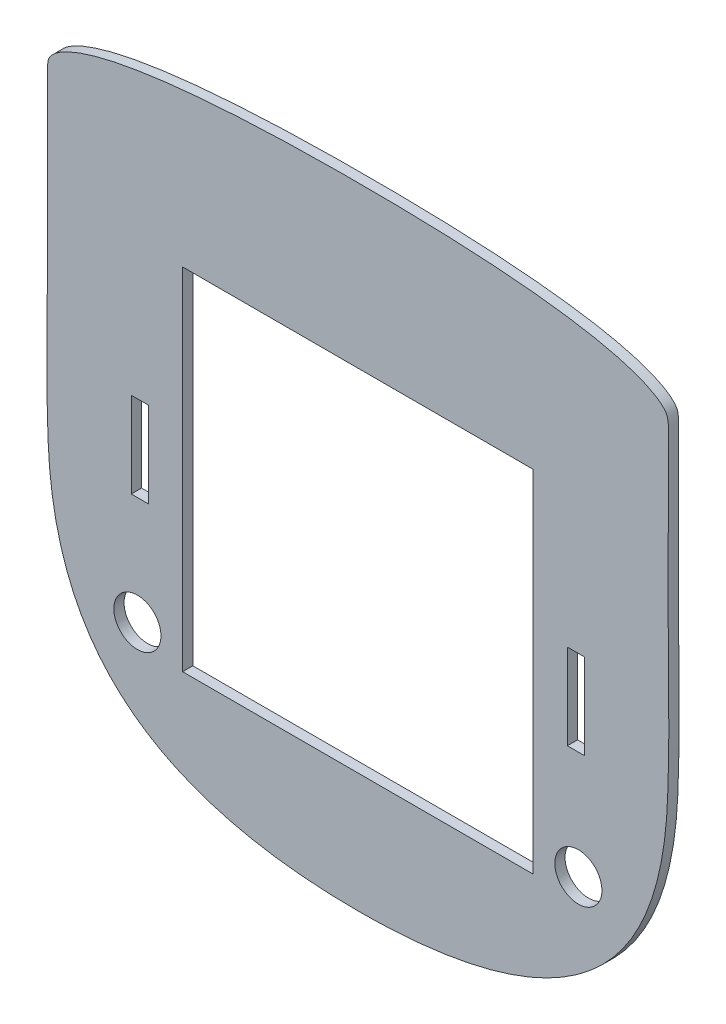
SolidWorks part; units mm, degrees
ref_plane "Front Plane" through (0, 0, 0) normal (0, 0, 1) x (1, 0, 0)
ref_plane "Top Plane" through (0, 0, 0) normal (0, 1, 0) x (1, 0, 0)
ref_plane "Right Plane" through (0, 0, 0) normal (1, 0, 0) x (0, 0, -1)
sketch "Sketch2" plane through (-0.2017, -72.2355, -2871.2971) normal (0, 0, 1) x (1, 0, 0)
  line L4 (52.07, 67.2522) -> (-52.07, 67.2522)
  line L5 (-52.07, 67.2522) -> (-52.07, -36.8878)
  line L6 (52.07, -36.8878) -> (52.07, 67.2522)
  line L7 (-52.07, -36.8878) -> (52.07, -36.8878)
  line L8 (0, 67.2522) -> (0, 47.5498)
  line L9 (-67.31, 26.6122) -> (-62.23, 26.6122)
  line L10 (-67.31, 26.6122) -> (-67.31, 1.2122)
  line L11 (-67.31, 1.2122) -> (-62.23, 1.2122)
  line L12 (-62.23, 26.6122) -> (-62.23, 1.2122)
  line L13 (67.31, 1.2122) -> (62.23, 1.2122)
  line L14 (67.31, 26.6122) -> (62.23, 26.6122)
  line L15 (62.23, 26.6122) -> (62.23, 1.2122)
  line L16 (67.31, 26.6122) -> (67.31, 1.2122)
  circle A3 centre (65.5, -30.8878) radius 7
  circle A4 centre (-65.5, -30.8878) radius 7
  spline S0 degree 3 poles (97.9117, 101.757) (98.0926, 100.5826) (98.1683, 99.8507) (98.201, 98.9643) (98.2056, 98.5204) (98.2033, 98.0762) (98.2036, 97.6318) (98.2026, 97.1872) (98.2018, 96.5942) (98.1997, 95.5557) (98.1964, 94.0701) (98.1912, 92.2844) (98.1853, 90.4955) (98.1786, 88.7035) (98.1713, 86.9085) (98.1636, 85.1105) (98.1554, 83.3094) (98.147, 81.5054) (98.1356, 79.096) (98.1213, 76.0769) (98.1051, 72.4424) (98.0908, 68.7965) (98.0796, 65.1394) (98.0728, 61.4713) (98.0711, 57.7925) (98.0753, 54.103) (98.0874, 50.4033) (98.1094, 46.6935) (98.1491, 41.7343) (98.2125, 35.5119) (98.2598, 28.01) (98.2502, 21.7312) (98.1939, 16.6943) (98.1345, 13.5409) (98.0699, 11.0154) (98.0125, 9.1199) (97.945, 7.2235) (97.8675, 5.3262) (97.778, 3.4282) (97.6786, 1.5298) (97.5624, -0.3688) (97.2739, -4.1659) (96.6367, -9.8576) (95.2643, -17.3922) (93.2832, -24.8169) (90.6142, -32.0401) (87.1877, -38.9585) (83.6766, -44.3599) (80.4862, -48.4025) (77.0545, -52.2409) (72.332, -56.6273) (66.103, -61.1882) (59.4287, -65.0467) (52.4324, -68.2445) (45.1957, -70.832) (37.7973, -72.8633) (30.2897, -74.3932) (22.7275, -75.4943) (12.6127, -76.4627) (5.0324, -76.7148) (-5.0355, -76.7148) (-12.6198, -76.4624) (-22.7388, -75.4931) (-30.3035, -74.391) (-37.8129, -72.8599) (-45.2125, -70.8272) (-52.4499, -68.238) (-59.4461, -65.0384) (-66.1196, -61.178) (-72.3471, -56.6154) (-77.0679, -52.2278) (-80.4981, -48.3887) (-83.6868, -44.3454) (-87.1957, -38.9438) (-90.6199, -32.0257) (-93.2868, -24.8034) (-95.2663, -17.38) (-96.6374, -9.847) (-97.2741, -4.1565) (-97.5622, -0.3603) (-97.6784, 1.5379) (-97.7779, 3.4359) (-97.8674, 5.3334) (-97.9449, 7.2303) (-98.0124, 9.1263) (-98.0698, 11.0213) (-98.1344, 13.5463) (-98.1939, 16.699) (-98.2502, 21.7349) (-98.2598, 28.0124) (-98.2124, 35.5129) (-98.1491, 41.7344) (-98.1094, 46.6929) (-98.0874, 50.4022) (-98.0753, 54.1015) (-98.0711, 57.7907) (-98.0728, 61.4693) (-98.0796, 65.1372) (-98.0908, 68.7942) (-98.1051, 72.44) (-98.1213, 76.0745) (-98.1356, 79.0937) (-98.147, 81.5032) (-98.1554, 83.3073) (-98.1636, 85.1085) (-98.1713, 86.9067) (-98.1786, 88.7018) (-98.1853, 90.494) (-98.1912, 92.283) (-98.1963, 94.069) (-98.1997, 95.5548) (-98.2018, 96.5934) (-98.2026, 97.1865) (-98.2036, 97.6312) (-98.2034, 98.0756) (-98.2056, 98.5199) (-98.201, 98.9639) (-98.1685, 99.8505) (-98.0927, 100.5825) (-97.9118, 101.7567) (-97.5911, 102.9272) (-96.7445, 104.5237) (-95.6284, 105.9307) (-94.3242, 107.1498) (-92.9089, 108.2104) (-90.9195, 109.4482) (-88.322, 110.7311) (-85.1289, 111.981) (-81.907, 113.0191) (-78.6797, 113.8993) (-75.4586, 114.6561) (-72.2483, 115.315) (-69.0513, 115.893) (-65.8677, 116.4036) (-62.6974, 116.856) (-59.5401, 117.2586) (-55.346, 117.7364) (-50.1305, 118.2378) (-43.9049, 118.7183) (-37.6983, 119.1001) (-31.4972, 119.4014) (-25.2861, 119.6319) (-19.0497, 119.8026) (-10.6783, 119.9573) (-4.3114, 120) (4.3116, 120) (10.6784, 119.9573) (19.0492, 119.8026) (25.285, 119.6319) (31.4954, 119.4014) (37.6957, 119.1003) (43.9016, 118.7185) (50.1264, 118.2381) (55.3414, 117.7368) (59.535, 117.2592) (62.6921, 116.8566) (65.8622, 116.4044) (69.0457, 115.8939) (72.2427, 115.316) (75.4529, 114.6572) (78.6742, 113.9005) (81.9018, 113.0204) (85.1241, 111.9825) (88.3177, 110.7327) (90.916, 109.4498) (92.906, 108.212) (94.3218, 107.1513) (95.6266, 105.9321) (96.7434, 104.5248) (97.5906, 102.9279) (97.9117, 101.757) (98.0926, 100.5826) (98.1683, 99.8507) knots -0.005356 -0.002678 0 0 0.002568 0.00321 0.003852 0.004494 0.005135 0.005777 0.006419 0.007703 0.010271 0.012839 0.015406 0.017974 0.020542 0.02311 0.025677 0.028245 0.030813 0.035948 0.041084 0.046219 0.051355 0.05649 0.061626 0.066761 0.071897 0.077032 0.082168 0.092439 0.10271 0.112981 0.118116 0.123252 0.125819 0.128387 0.130955 0.133522 0.13609 0.138658 0.141226 0.143793 0.154064 0.164335 0.174606 0.184877 0.195148 0.205419 0.210555 0.21569 0.225961 0.236232 0.246503 0.256774 0.267045 0.277316 0.287587 0.297858 0.308129 0.328671 0.328671 0.349207 0.359475 0.369743 0.380011 0.390279 0.400547 0.410816 0.421084 0.431352 0.44162 0.446754 0.451888 0.462156 0.472424 0.482692 0.492961 0.503229 0.513497 0.516064 0.518631 0.521198 0.523765 0.526332 0.528899 0.531466 0.534033 0.539167 0.544301 0.554569 0.564837 0.575105 0.580239 0.585374 0.590508 0.595642 0.600776 0.60591 0.611044 0.616178 0.621312 0.626446 0.629013 0.63158 0.634147 0.636714 0.639281 0.641848 0.644415 0.646982 0.649549 0.650833 0.651475 0.652116 0.652758 0.6534 0.654042 0.654683 0.65725 0.65725 0.659928 0.662606 0.665283 0.667961 0.670639 0.673317 0.678672 0.684027 0.689383 0.694738 0.700094 0.705449 0.710804 0.71616 0.721515 0.726871 0.732226 0.742937 0.753648 0.764359 0.775069 0.78578 0.796491 0.807202 0.828623 0.828623 0.850045 0.860757 0.871468 0.882179 0.89289 0.903601 0.914312 0.925023 0.930378 0.935734 0.941089 0.946445 0.9518 0.957156 0.962511 0.967867 0.973222 0.978578 0.983933 0.986611 0.989289 0.991967 0.994644 0.997322 1 1 1.002568 1.00321 1.003852 only from (98.0041, 101.1575) to (98.0041, 101.1575)
  spline S1 degree 3 poles (97.9117, 101.757) (98.0926, 100.5826) (98.1683, 99.8507) (98.201, 98.9643) (98.2056, 98.5204) (98.2033, 98.0762) (98.2036, 97.6318) (98.2026, 97.1872) (98.2018, 96.5942) (98.1997, 95.5557) (98.1964, 94.0701) (98.1912, 92.2844) (98.1853, 90.4955) (98.1786, 88.7035) (98.1713, 86.9085) (98.1636, 85.1105) (98.1554, 83.3094) (98.147, 81.5054) (98.1356, 79.096) (98.1213, 76.0769) (98.1051, 72.4424) (98.0908, 68.7965) (98.0796, 65.1394) (98.0728, 61.4713) (98.0711, 57.7925) (98.0753, 54.103) (98.0874, 50.4033) (98.1094, 46.6935) (98.1491, 41.7343) (98.2125, 35.5119) (98.2598, 28.01) (98.2502, 21.7312) (98.1939, 16.6943) (98.1345, 13.5409) (98.0699, 11.0154) (98.0125, 9.1199) (97.945, 7.2235) (97.8675, 5.3262) (97.778, 3.4282) (97.6786, 1.5298) (97.5624, -0.3688) (97.2739, -4.1659) (96.6367, -9.8576) (95.2643, -17.3922) (93.2832, -24.8169) (90.6142, -32.0401) (87.1877, -38.9585) (83.6766, -44.3599) (80.4862, -48.4025) (77.0545, -52.2409) (72.332, -56.6273) (66.103, -61.1882) (59.4287, -65.0467) (52.4324, -68.2445) (45.1957, -70.832) (37.7973, -72.8633) (30.2897, -74.3932) (22.7275, -75.4943) (12.6127, -76.4627) (5.0324, -76.7148) (-5.0355, -76.7148) (-12.6198, -76.4624) (-22.7388, -75.4931) (-30.3035, -74.391) (-37.8129, -72.8599) (-45.2125, -70.8272) (-52.4499, -68.238) (-59.4461, -65.0384) (-66.1196, -61.178) (-72.3471, -56.6154) (-77.0679, -52.2278) (-80.4981, -48.3887) (-83.6868, -44.3454) (-87.1957, -38.9438) (-90.6199, -32.0257) (-93.2868, -24.8034) (-95.2663, -17.38) (-96.6374, -9.847) (-97.2741, -4.1565) (-97.5622, -0.3603) (-97.6784, 1.5379) (-97.7779, 3.4359) (-97.8674, 5.3334) (-97.9449, 7.2303) (-98.0124, 9.1263) (-98.0698, 11.0213) (-98.1344, 13.5463) (-98.1939, 16.699) (-98.2502, 21.7349) (-98.2598, 28.0124) (-98.2124, 35.5129) (-98.1491, 41.7344) (-98.1094, 46.6929) (-98.0874, 50.4022) (-98.0753, 54.1015) (-98.0711, 57.7907) (-98.0728, 61.4693) (-98.0796, 65.1372) (-98.0908, 68.7942) (-98.1051, 72.44) (-98.1213, 76.0745) (-98.1356, 79.0937) (-98.147, 81.5032) (-98.1554, 83.3073) (-98.1636, 85.1085) (-98.1713, 86.9067) (-98.1786, 88.7018) (-98.1853, 90.494) (-98.1912, 92.283) (-98.1963, 94.069) (-98.1997, 95.5548) (-98.2018, 96.5934) (-98.2026, 97.1865) (-98.2036, 97.6312) (-98.2034, 98.0756) (-98.2056, 98.5199) (-98.201, 98.9639) (-98.1685, 99.8505) (-98.0927, 100.5825) (-97.9118, 101.7567) (-97.5911, 102.9272) (-96.7445, 104.5237) (-95.6284, 105.9307) (-94.3242, 107.1498) (-92.9089, 108.2104) (-90.9195, 109.4482) (-88.322, 110.7311) (-85.1289, 111.981) (-81.907, 113.0191) (-78.6797, 113.8993) (-75.4586, 114.6561) (-72.2483, 115.315) (-69.0513, 115.893) (-65.8677, 116.4036) (-62.6974, 116.856) (-59.5401, 117.2586) (-55.346, 117.7364) (-50.1305, 118.2378) (-43.9049, 118.7183) (-37.6983, 119.1001) (-31.4972, 119.4014) (-25.2861, 119.6319) (-19.0497, 119.8026) (-10.6783, 119.9573) (-4.3114, 120) (4.3116, 120) (10.6784, 119.9573) (19.0492, 119.8026) (25.285, 119.6319) (31.4954, 119.4014) (37.6957, 119.1003) (43.9016, 118.7185) (50.1264, 118.2381) (55.3414, 117.7368) (59.535, 117.2592) (62.6921, 116.8566) (65.8622, 116.4044) (69.0457, 115.8939) (72.2427, 115.316) (75.4529, 114.6572) (78.6742, 113.9005) (81.9018, 113.0204) (85.1241, 111.9825) (88.3177, 110.7327) (90.916, 109.4498) (92.906, 108.212) (94.3218, 107.1513) (95.6266, 105.9321) (96.7434, 104.5248) (97.5906, 102.9279) (97.9117, 101.757) (98.0926, 100.5826) (98.1683, 99.8507) knots -0.005356 -0.002678 0 0 0.002568 0.00321 0.003852 0.004494 0.005135 0.005777 0.006419 0.007703 0.010271 0.012839 0.015406 0.017974 0.020542 0.02311 0.025677 0.028245 0.030813 0.035948 0.041084 0.046219 0.051355 0.05649 0.061626 0.066761 0.071897 0.077032 0.082168 0.092439 0.10271 0.112981 0.118116 0.123252 0.125819 0.128387 0.130955 0.133522 0.13609 0.138658 0.141226 0.143793 0.154064 0.164335 0.174606 0.184877 0.195148 0.205419 0.210555 0.21569 0.225961 0.236232 0.246503 0.256774 0.267045 0.277316 0.287587 0.297858 0.308129 0.328671 0.328671 0.349207 0.359475 0.369743 0.380011 0.390279 0.400547 0.410816 0.421084 0.431352 0.44162 0.446754 0.451888 0.462156 0.472424 0.482692 0.492961 0.503229 0.513497 0.516064 0.518631 0.521198 0.523765 0.526332 0.528899 0.531466 0.534033 0.539167 0.544301 0.554569 0.564837 0.575105 0.580239 0.585374 0.590508 0.595642 0.600776 0.60591 0.611044 0.616178 0.621312 0.626446 0.629013 0.63158 0.634147 0.636714 0.639281 0.641848 0.644415 0.646982 0.649549 0.650833 0.651475 0.652116 0.652758 0.6534 0.654042 0.654683 0.65725 0.65725 0.659928 0.662606 0.665283 0.667961 0.670639 0.673317 0.678672 0.684027 0.689383 0.694738 0.700094 0.705449 0.710804 0.71616 0.721515 0.726871 0.732226 0.742937 0.753648 0.764359 0.775069 0.78578 0.796491 0.807202 0.828623 0.828623 0.850045 0.860757 0.871468 0.882179 0.89289 0.903601 0.914312 0.925023 0.930378 0.935734 0.941089 0.946445 0.9518 0.957156 0.962511 0.967867 0.973222 0.978578 0.983933 0.986611 0.989289 0.991967 0.994644 0.997322 1 1 1.002568 1.00321 1.003852 only from (98.0041, 101.1575) to (98.0041, 101.1575)
extrude "Boss-Extrude1" add sketch "Sketch2" along normal blind 3.048
sketch "Sketch8" plane through (0, 0, -2871.2971) normal (0, 0, -1) x (-1, 0, 0)
  spline S0 degree 3 poles (0.3104, -144.6233) (-3.2745, -144.6233) (-6.7385, -144.5374) (-13.6391, -144.1734) (-17.0759, -143.8967) (-23.9172, -143.1176) (-27.3217, -142.6152) (-34.0916, -141.3359) (-37.4568, -140.5583) (-42.4676, -139.1325) (-44.132, -138.6136) (-47.4451, -137.4763) (-49.0791, -136.8629) (-53.907, -134.8756) (-57.0275, -133.356) (-61.5302, -130.7241) (-63.0014, -129.7878) (-65.1579, -128.2838) (-65.8686, -127.7656) (-67.2588, -126.7056) (-67.9401, -126.1626) (-71.2775, -123.3816) (-73.7252, -120.9462) (-77.049, -116.9634) (-78.0997, -115.5815) (-79.5891, -113.4266) (-80.0721, -112.6932) (-81.0049, -111.2054) (-81.4532, -110.4536) (-83.6073, -106.6558) (-85.0532, -103.4958) (-86.8753, -98.6036) (-87.4246, -96.9473) (-88.1682, -94.4276) (-88.4026, -93.582) (-88.8431, -91.8912) (-89.0495, -91.0445) (-90.0179, -86.8057) (-90.5896, -83.3964) (-91.2148, -78.2615) (-91.3841, -76.5464) (-91.6545, -73.1101) (-91.754, -71.3887) (-91.898, -67.941) (-91.9539, -66.2157) (-92.0471, -62.7634) (-92.0825, -61.0363) (-92.2165, -52.3967) (-92.1817, -45.472) (-92.0888, -35.0908) (-92.0506, -31.6304) (-91.9891, -24.7096) (-91.9673, -21.2491) (-91.9354, -10.8677) (-91.9508, -3.9467) (-91.9892, 6.4348) (-92.0052, 9.8952) (-92.0303, 16.8162) (-92.042, 20.2767) (-92.0525, 24.1698) (-92.0537, 24.6023) (-92.0553, 25.2512) (-92.0564, 25.4675) (-92.0572, 25.9001) (-92.0571, 26.1163) (-92.027, 26.7631) (-91.9788, 27.1925) (-91.8893, 27.7273) (-91.8701, 27.8341) (-91.8289, 28.0477) (-91.8082, 28.1544) (-91.727, 28.4674) (-91.6523, 28.6684) (-91.4689, 29.0577) (-91.3594, 29.2474) (-91.118, 29.6064) (-90.9865, 29.7765) (-90.5682, 30.2665) (-90.2568, 30.5679) (-89.6014, 31.1295) (-89.2598, 31.3875) (-88.558, 31.8727) (-88.1978, 32.1002) (-87.0967, 32.7488) (-86.3351, 33.1358) (-84.7773, 33.8532) (-83.9869, 34.1795) (-81.6013, 35.0885) (-79.9866, 35.6037) (-76.7294, 36.5288) (-75.0863, 36.9373) (-71.7803, 37.6791) (-70.1172, 38.0123) (-66.7762, 38.6228) (-65.0971, 38.8997) (-61.7373, 39.4079) (-60.0554, 39.6394) (-55.0048, 40.2786) (-51.6313, 40.6319) (-44.8751, 41.2367) (-41.4925, 41.4873) (-31.334, 42.1214) (-24.5441, 42.3893) (-10.9746, 42.7178) (-4.1923, 42.7779) (9.3686, 42.7388) (16.1472, 42.6362) (29.6992, 42.2045) (36.4726, 41.8779) (46.6267, 41.1254) (50.0104, 40.83) (56.775, 40.1185) (60.1495, 39.7032) (66.8744, 38.6973) (70.2267, 38.1082) (75.2058, 37.0053) (76.8591, 36.5997) (80.1333, 35.6825) (81.7572, 35.1715) (84.146, 34.277) (84.9331, 33.958) (86.4814, 33.2608) (87.2446, 32.8832) (88.7241, 32.0392) (89.4378, 31.5786) (90.4316, 30.7738) (90.7488, 30.4866) (91.1842, 30.021) (91.3228, 29.8597) (91.5827, 29.5206) (91.7035, 29.3429) (91.9149, 28.9754) (92.0068, 28.785) (92.1183, 28.4865) (92.151, 28.3848) (92.2066, 28.1766) (92.2275, 28.0719) (92.3293, 27.5487) (92.3916, 27.129) (92.4435, 26.497) (92.4552, 26.286) (92.462, 25.8631) (92.4603, 25.6514) (92.4581, 25.0163) (92.4573, 24.5929) (92.4509, 22.4759) (92.446, 20.7824) (92.4295, 15.7018) (92.4176, 12.3147) (92.3895, 5.5405) (92.3758, 2.1534) (92.3457, -8.0078) (92.3404, -14.7819) (92.3933, -24.943) (92.4234, -28.33) (92.4902, -35.104) (92.5259, -38.491) (92.5994, -48.6509) (92.6051, -55.4224) (92.4234, -63.8791) (92.377, -65.57) (92.2618, -68.951) (92.1963, -70.6411) (91.8939, -75.7072) (91.5681, -79.0796) (90.8372, -84.1282) (90.5529, -85.8095) (89.8913, -89.1681) (89.5159, -90.8346) (88.2444, -95.7791) (87.2025, -99.0074) (85.2859, -103.7263) (84.588, -105.2785) (83.4426, -107.5724) (83.0436, -108.3327) (82.2145, -109.8346) (81.7857, -110.5738) (79.5701, -114.2106) (77.5707, -116.9323) (74.2241, -120.7274) (73.0499, -121.9439) (71.2012, -123.6964) (70.5705, -124.2686) (69.28, -125.389) (68.6186, -125.9384) (65.2622, -128.6077) (62.4266, -130.489) (57.9836, -132.9907) (56.4711, -133.7714) (54.1587, -134.8688) (53.3806, -135.2223) (51.8105, -135.9056) (51.0184, -136.2353) (47.0494, -137.8175) (43.8265, -138.8806) (37.3066, -140.6915) (34.0094, -141.4387) (27.3538, -142.6729) (23.9957, -143.1607) (18.92, -143.7292) (17.2207, -143.8913) (13.8228, -144.1646) (12.1227, -144.2762) (8.7203, -144.4525) (7.018, -144.5172) (4.4631, -144.5813) (3.1852, -144.6051) (1.6937, -144.6188) (0.9478, -144.6222) (0.6281, -144.6229) (0.4149, -144.6232) (0.3104, -144.6233) (-3.2745, -144.6233) (-6.7385, -144.5374) knots -0.000488 -0.000488 0 0 0.015625 0.015625 0.03125 0.03125 0.046875 0.046875 0.0625 0.0625 0.070312 0.070312 0.078125 0.078125 0.09375 0.09375 0.101562 0.101562 0.105469 0.105469 0.109375 0.109375 0.125 0.125 0.132812 0.132812 0.136719 0.136719 0.140625 0.140625 0.15625 0.15625 0.164062 0.164062 0.167969 0.167969 0.171875 0.171875 0.1875 0.1875 0.195312 0.195312 0.203125 0.203125 0.210937 0.210937 0.21875 0.21875 0.25 0.25 0.265625 0.265625 0.28125 0.28125 0.3125 0.3125 0.328125 0.328125 0.34375 0.34375 0.345703 0.345703 0.34668 0.34668 0.347656 0.347656 0.349609 0.349609 0.350098 0.350098 0.350586 0.350586 0.351563 0.351563 0.352539 0.352539 0.353516 0.353516 0.355469 0.355469 0.357422 0.357422 0.359375 0.359375 0.363281 0.363281 0.367187 0.367187 0.375 0.375 0.382812 0.382812 0.390625 0.390625 0.398437 0.398437 0.40625 0.40625 0.421875 0.421875 0.4375 0.4375 0.46875 0.46875 0.5 0.5 0.53125 0.53125 0.5625 0.5625 0.578125 0.578125 0.59375 0.59375 0.609375 0.609375 0.617187 0.617187 0.625 0.625 0.628906 0.628906 0.632812 0.632812 0.636719 0.636719 0.638672 0.638672 0.639648 0.639648 0.640625 0.640625 0.641602 0.641602 0.64209 0.64209 0.642578 0.642578 0.644531 0.644531 0.645508 0.645508 0.646484 0.646484 0.648437 0.648437 0.65625 0.65625 0.671875 0.671875 0.6875 0.6875 0.71875 0.71875 0.734375 0.734375 0.75 0.75 0.78125 0.78125 0.789063 0.789063 0.796875 0.796875 0.8125 0.8125 0.820313 0.820313 0.828125 0.828125 0.84375 0.84375 0.851563 0.851563 0.855469 0.855469 0.859375 0.859375 0.875 0.875 0.882813 0.882813 0.886719 0.886719 0.890625 0.890625 0.90625 0.90625 0.914063 0.914063 0.917969 0.917969 0.921875 0.921875 0.9375 0.9375 0.953125 0.953125 0.96875 0.96875 0.976563 0.976563 0.984375 0.984375 0.992188 0.992188 0.996094 0.998047 0.999023 0.999512 0.999512 1 1 1.015625 1.015625 1.03125 only from (0.2017, -144.6233) to (0.2017, -144.6233)
  spline S1 degree 3 poles (0.3104, -144.6233) (-3.2745, -144.6233) (-6.7385, -144.5374) (-13.6391, -144.1734) (-17.0759, -143.8967) (-23.9172, -143.1176) (-27.3217, -142.6152) (-34.0916, -141.3359) (-37.4568, -140.5583) (-42.4676, -139.1325) (-44.132, -138.6136) (-47.4451, -137.4763) (-49.0791, -136.8629) (-53.907, -134.8756) (-57.0275, -133.356) (-61.5302, -130.7241) (-63.0014, -129.7878) (-65.1579, -128.2838) (-65.8686, -127.7656) (-67.2588, -126.7056) (-67.9401, -126.1626) (-71.2775, -123.3816) (-73.7252, -120.9462) (-77.049, -116.9634) (-78.0997, -115.5815) (-79.5891, -113.4266) (-80.0721, -112.6932) (-81.0049, -111.2054) (-81.4532, -110.4536) (-83.6073, -106.6558) (-85.0532, -103.4958) (-86.8753, -98.6036) (-87.4246, -96.9473) (-88.1682, -94.4276) (-88.4026, -93.582) (-88.8431, -91.8912) (-89.0495, -91.0445) (-90.0179, -86.8057) (-90.5896, -83.3964) (-91.2148, -78.2615) (-91.3841, -76.5464) (-91.6545, -73.1101) (-91.754, -71.3887) (-91.898, -67.941) (-91.9539, -66.2157) (-92.0471, -62.7634) (-92.0825, -61.0363) (-92.2165, -52.3967) (-92.1817, -45.472) (-92.0888, -35.0908) (-92.0506, -31.6304) (-91.9891, -24.7096) (-91.9673, -21.2491) (-91.9354, -10.8677) (-91.9508, -3.9467) (-91.9892, 6.4348) (-92.0052, 9.8952) (-92.0303, 16.8162) (-92.042, 20.2767) (-92.0525, 24.1698) (-92.0537, 24.6023) (-92.0553, 25.2512) (-92.0564, 25.4675) (-92.0572, 25.9001) (-92.0571, 26.1163) (-92.027, 26.7631) (-91.9788, 27.1925) (-91.8893, 27.7273) (-91.8701, 27.8341) (-91.8289, 28.0477) (-91.8082, 28.1544) (-91.727, 28.4674) (-91.6523, 28.6684) (-91.4689, 29.0577) (-91.3594, 29.2474) (-91.118, 29.6064) (-90.9865, 29.7765) (-90.5682, 30.2665) (-90.2568, 30.5679) (-89.6014, 31.1295) (-89.2598, 31.3875) (-88.558, 31.8727) (-88.1978, 32.1002) (-87.0967, 32.7488) (-86.3351, 33.1358) (-84.7773, 33.8532) (-83.9869, 34.1795) (-81.6013, 35.0885) (-79.9866, 35.6037) (-76.7294, 36.5288) (-75.0863, 36.9373) (-71.7803, 37.6791) (-70.1172, 38.0123) (-66.7762, 38.6228) (-65.0971, 38.8997) (-61.7373, 39.4079) (-60.0554, 39.6394) (-55.0048, 40.2786) (-51.6313, 40.6319) (-44.8751, 41.2367) (-41.4925, 41.4873) (-31.334, 42.1214) (-24.5441, 42.3893) (-10.9746, 42.7178) (-4.1923, 42.7779) (9.3686, 42.7388) (16.1472, 42.6362) (29.6992, 42.2045) (36.4726, 41.8779) (46.6267, 41.1254) (50.0104, 40.83) (56.775, 40.1185) (60.1495, 39.7032) (66.8744, 38.6973) (70.2267, 38.1082) (75.2058, 37.0053) (76.8591, 36.5997) (80.1333, 35.6825) (81.7572, 35.1715) (84.146, 34.277) (84.9331, 33.958) (86.4814, 33.2608) (87.2446, 32.8832) (88.7241, 32.0392) (89.4378, 31.5786) (90.4316, 30.7738) (90.7488, 30.4866) (91.1842, 30.021) (91.3228, 29.8597) (91.5827, 29.5206) (91.7035, 29.3429) (91.9149, 28.9754) (92.0068, 28.785) (92.1183, 28.4865) (92.151, 28.3848) (92.2066, 28.1766) (92.2275, 28.0719) (92.3293, 27.5487) (92.3916, 27.129) (92.4435, 26.497) (92.4552, 26.286) (92.462, 25.8631) (92.4603, 25.6514) (92.4581, 25.0163) (92.4573, 24.5929) (92.4509, 22.4759) (92.446, 20.7824) (92.4295, 15.7018) (92.4176, 12.3147) (92.3895, 5.5405) (92.3758, 2.1534) (92.3457, -8.0078) (92.3404, -14.7819) (92.3933, -24.943) (92.4234, -28.33) (92.4902, -35.104) (92.5259, -38.491) (92.5994, -48.6509) (92.6051, -55.4224) (92.4234, -63.8791) (92.377, -65.57) (92.2618, -68.951) (92.1963, -70.6411) (91.8939, -75.7072) (91.5681, -79.0796) (90.8372, -84.1282) (90.5529, -85.8095) (89.8913, -89.1681) (89.5159, -90.8346) (88.2444, -95.7791) (87.2025, -99.0074) (85.2859, -103.7263) (84.588, -105.2785) (83.4426, -107.5724) (83.0436, -108.3327) (82.2145, -109.8346) (81.7857, -110.5738) (79.5701, -114.2106) (77.5707, -116.9323) (74.2241, -120.7274) (73.0499, -121.9439) (71.2012, -123.6964) (70.5705, -124.2686) (69.28, -125.389) (68.6186, -125.9384) (65.2622, -128.6077) (62.4266, -130.489) (57.9836, -132.9907) (56.4711, -133.7714) (54.1587, -134.8688) (53.3806, -135.2223) (51.8105, -135.9056) (51.0184, -136.2353) (47.0494, -137.8175) (43.8265, -138.8806) (37.3066, -140.6915) (34.0094, -141.4387) (27.3538, -142.6729) (23.9957, -143.1607) (18.92, -143.7292) (17.2207, -143.8913) (13.8228, -144.1646) (12.1227, -144.2762) (8.7203, -144.4525) (7.018, -144.5172) (4.4631, -144.5813) (3.1852, -144.6051) (1.6937, -144.6188) (0.9478, -144.6222) (0.6281, -144.6229) (0.4149, -144.6232) (0.3104, -144.6233) (-3.2745, -144.6233) (-6.7385, -144.5374) knots -0.000488 -0.000488 0 0 0.015625 0.015625 0.03125 0.03125 0.046875 0.046875 0.0625 0.0625 0.070312 0.070312 0.078125 0.078125 0.09375 0.09375 0.101562 0.101562 0.105469 0.105469 0.109375 0.109375 0.125 0.125 0.132812 0.132812 0.136719 0.136719 0.140625 0.140625 0.15625 0.15625 0.164062 0.164062 0.167969 0.167969 0.171875 0.171875 0.1875 0.1875 0.195312 0.195312 0.203125 0.203125 0.210937 0.210937 0.21875 0.21875 0.25 0.25 0.265625 0.265625 0.28125 0.28125 0.3125 0.3125 0.328125 0.328125 0.34375 0.34375 0.345703 0.345703 0.34668 0.34668 0.347656 0.347656 0.349609 0.349609 0.350098 0.350098 0.350586 0.350586 0.351563 0.351563 0.352539 0.352539 0.353516 0.353516 0.355469 0.355469 0.357422 0.357422 0.359375 0.359375 0.363281 0.363281 0.367187 0.367187 0.375 0.375 0.382812 0.382812 0.390625 0.390625 0.398437 0.398437 0.40625 0.40625 0.421875 0.421875 0.4375 0.4375 0.46875 0.46875 0.5 0.5 0.53125 0.53125 0.5625 0.5625 0.578125 0.578125 0.59375 0.59375 0.609375 0.609375 0.617187 0.617187 0.625 0.625 0.628906 0.628906 0.632812 0.632812 0.636719 0.636719 0.638672 0.638672 0.639648 0.639648 0.640625 0.640625 0.641602 0.641602 0.64209 0.64209 0.642578 0.642578 0.644531 0.644531 0.645508 0.645508 0.646484 0.646484 0.648437 0.648437 0.65625 0.65625 0.671875 0.671875 0.6875 0.6875 0.71875 0.71875 0.734375 0.734375 0.75 0.75 0.78125 0.78125 0.789063 0.789063 0.796875 0.796875 0.8125 0.8125 0.820313 0.820313 0.828125 0.828125 0.84375 0.84375 0.851563 0.851563 0.855469 0.855469 0.859375 0.859375 0.875 0.875 0.882813 0.882813 0.886719 0.886719 0.890625 0.890625 0.90625 0.90625 0.914063 0.914063 0.917969 0.917969 0.921875 0.921875 0.9375 0.9375 0.953125 0.953125 0.96875 0.96875 0.976563 0.976563 0.984375 0.984375 0.992188 0.992188 0.996094 0.998047 0.999023 0.999512 0.999512 1 1 1.015625 1.015625 1.03125 only from (0.2017, -144.6233) to (0.2017, -144.6233)
  spline S2 degree 3 poles (-97.8023, 28.922) (-97.8909, 28.3471) (-97.9665, 27.6153) (-97.9993, 26.7288) (-98.0038, 26.2849) (-98.0016, 25.8407) (-98.0019, 25.3963) (-98.0008, 24.9517) (-98, 24.3587) (-97.998, 23.3202) (-97.9946, 21.8347) (-97.9895, 20.0489) (-97.9836, 18.26) (-97.9769, 16.4681) (-97.9696, 14.6731) (-97.9618, 12.875) (-97.9537, 11.074) (-97.9452, 9.2699) (-97.9338, 6.8605) (-97.9195, 3.8415) (-97.9033, 0.207) (-97.889, -3.4389) (-97.8778, -7.096) (-97.871, -10.7641) (-97.8693, -14.443) (-97.8735, -18.1325) (-97.8857, -21.8322) (-97.9077, -25.5419) (-97.9474, -30.5011) (-98.0107, -36.7236) (-98.058, -44.2255) (-98.0485, -50.5042) (-97.9922, -55.5411) (-97.9327, -58.6945) (-97.8682, -61.2201) (-97.8107, -63.1155) (-97.7432, -65.012) (-97.6658, -66.9093) (-97.5763, -68.8072) (-97.4769, -70.7056) (-97.3606, -72.6043) (-97.0721, -76.4014) (-96.4349, -82.0931) (-95.0625, -89.6277) (-93.0815, -97.0524) (-90.4124, -104.2756) (-86.9859, -111.1939) (-83.4748, -116.5953) (-80.2845, -120.638) (-76.8527, -124.4764) (-72.1302, -128.8628) (-65.9013, -133.4237) (-59.2269, -137.2821) (-52.2307, -140.4799) (-44.9939, -143.0674) (-37.5956, -145.0987) (-30.088, -146.6286) (-22.5258, -147.7297) (-12.4109, -148.6982) (-4.8306, -148.9503) (5.2372, -148.9503) (12.8215, -148.6979) (22.9405, -147.7285) (30.5052, -146.6265) (38.0147, -145.0954) (45.4143, -143.0627) (52.6516, -140.4735) (59.6478, -137.2739) (66.3214, -133.4135) (72.5488, -128.8509) (77.2696, -124.4632) (80.6998, -120.6241) (83.8885, -116.5809) (87.3975, -111.1792) (90.8216, -104.2612) (93.4886, -97.0389) (95.468, -89.6155) (96.8392, -82.0824) (97.4758, -76.392) (97.764, -72.5958) (97.8801, -70.6976) (97.9796, -68.7996) (98.0691, -66.9021) (98.1466, -65.0052) (98.2141, -63.1092) (98.2716, -61.2142) (98.3362, -58.6892) (98.3956, -55.5365) (98.4519, -50.5006) (98.4615, -44.2231) (98.4142, -36.7225) (98.3508, -30.5011) (98.3112, -25.5425) (98.2891, -21.8333) (98.277, -18.1339) (98.2728, -14.4448) (98.2745, -10.7662) (98.2813, -7.0983) (98.2925, -3.4413) (98.3068, 0.2046) (98.323, 3.8391) (98.3373, 6.8582) (98.3487, 9.2677) (98.3571, 11.0719) (98.3653, 12.873) (98.3731, 14.6712) (98.3804, 16.4664) (98.387, 18.2585) (98.393, 20.0476) (98.3981, 21.8336) (98.4015, 23.3193) (98.4035, 24.358) (98.4043, 24.9511) (98.4053, 25.3957) (98.4051, 25.8402) (98.4074, 26.2845) (98.4027, 26.7284) (98.3702, 27.6151) (98.2944, 28.347) (98.1136, 29.5212) (97.7928, 30.6917) (96.9462, 32.2883) (95.8301, 33.6952) (94.5259, 34.9144) (93.1107, 35.9749) (91.1213, 37.2128) (88.5237, 38.4957) (85.3307, 39.7455) (82.1088, 40.7836) (78.8814, 41.6639) (75.6603, 42.4206) (72.4501, 43.0795) (69.253, 43.6575) (66.0694, 44.1682) (62.8991, 44.6205) (59.7418, 45.0231) (55.5478, 45.5009) (50.3322, 46.0023) (44.1066, 46.4828) (37.9, 46.8647) (31.6989, 47.1659) (25.4878, 47.3964) (19.2514, 47.5671) (10.88, 47.7218) (4.5131, 47.7645) (-4.1098, 47.7645) (-10.4766, 47.7218) (-18.8475, 47.5671) (-25.0833, 47.3964) (-31.2937, 47.166) (-37.494, 46.8648) (-43.6998, 46.483) (-49.9247, 46.0027) (-55.1396, 45.5013) (-59.3333, 45.0237) (-62.4904, 44.6212) (-65.6605, 44.1689) (-68.8439, 43.6584) (-72.0409, 43.0805) (-75.2512, 42.4217) (-78.4724, 41.6651) (-81.7001, 40.785) (-84.9224, 39.747) (-88.116, 38.4972) (-90.7142, 37.2144) (-92.7043, 35.9765) (-94.12, 34.9159) (-95.4248, 33.6966) (-96.5416, 32.2894) (-97.3889, 30.6924) (-97.71, 29.5215) (-97.8023, 28.922) (-97.8909, 28.3471) (-97.9665, 27.6153) knots -0.002678 0 0 0 0.002568 0.00321 0.003852 0.004494 0.005135 0.005777 0.006419 0.007703 0.010271 0.012839 0.015406 0.017974 0.020542 0.02311 0.025677 0.028245 0.030813 0.035948 0.041084 0.046219 0.051355 0.05649 0.061626 0.066761 0.071897 0.077032 0.082168 0.092439 0.10271 0.112981 0.118116 0.123252 0.125819 0.128387 0.130955 0.133522 0.13609 0.138658 0.141226 0.143793 0.154064 0.164335 0.174606 0.184877 0.195148 0.205419 0.210555 0.21569 0.225961 0.236232 0.246503 0.256774 0.267045 0.277316 0.287587 0.297858 0.308129 0.328671 0.328671 0.349207 0.359475 0.369743 0.380011 0.390279 0.400547 0.410816 0.421084 0.431352 0.44162 0.446754 0.451888 0.462156 0.472424 0.482692 0.492961 0.503229 0.513497 0.516064 0.518631 0.521198 0.523765 0.526332 0.528899 0.531466 0.534033 0.539167 0.544301 0.554569 0.564837 0.575105 0.580239 0.585374 0.590508 0.595642 0.600776 0.60591 0.611044 0.616178 0.621312 0.626446 0.629013 0.63158 0.634147 0.636714 0.639281 0.641848 0.644415 0.646982 0.649549 0.650833 0.651475 0.652116 0.652758 0.6534 0.654042 0.654683 0.65725 0.65725 0.659928 0.662606 0.665283 0.667961 0.670639 0.673317 0.678672 0.684027 0.689383 0.694738 0.700094 0.705449 0.710804 0.71616 0.721515 0.726871 0.732226 0.742937 0.753648 0.764359 0.775069 0.78578 0.796491 0.807202 0.828623 0.828623 0.850045 0.860757 0.871468 0.882179 0.89289 0.903601 0.914312 0.925023 0.930378 0.935734 0.941089 0.946445 0.9518 0.957156 0.962511 0.967867 0.973222 0.978578 0.983933 0.986611 0.989289 0.991967 0.994644 0.997322 1 1 1 1.002568 1.00321 1.003852 only from (-97.8023, 28.922) to (-97.8023, 28.922) construction
  spline S3 degree 3 poles (-97.8023, 28.922) (-97.8909, 28.3471) (-97.9665, 27.6153) (-97.9993, 26.7288) (-98.0038, 26.2849) (-98.0016, 25.8407) (-98.0019, 25.3963) (-98.0008, 24.9517) (-98, 24.3587) (-97.998, 23.3202) (-97.9946, 21.8347) (-97.9895, 20.0489) (-97.9836, 18.26) (-97.9769, 16.4681) (-97.9696, 14.6731) (-97.9618, 12.875) (-97.9537, 11.074) (-97.9452, 9.2699) (-97.9338, 6.8605) (-97.9195, 3.8415) (-97.9033, 0.207) (-97.889, -3.4389) (-97.8778, -7.096) (-97.871, -10.7641) (-97.8693, -14.443) (-97.8735, -18.1325) (-97.8857, -21.8322) (-97.9077, -25.5419) (-97.9474, -30.5011) (-98.0107, -36.7236) (-98.058, -44.2255) (-98.0485, -50.5042) (-97.9922, -55.5411) (-97.9327, -58.6945) (-97.8682, -61.2201) (-97.8107, -63.1155) (-97.7432, -65.012) (-97.6658, -66.9093) (-97.5763, -68.8072) (-97.4769, -70.7056) (-97.3606, -72.6043) (-97.0721, -76.4014) (-96.4349, -82.0931) (-95.0625, -89.6277) (-93.0815, -97.0524) (-90.4124, -104.2756) (-86.9859, -111.1939) (-83.4748, -116.5953) (-80.2845, -120.638) (-76.8527, -124.4764) (-72.1302, -128.8628) (-65.9013, -133.4237) (-59.2269, -137.2821) (-52.2307, -140.4799) (-44.9939, -143.0674) (-37.5956, -145.0987) (-30.088, -146.6286) (-22.5258, -147.7297) (-12.4109, -148.6982) (-4.8306, -148.9503) (5.2372, -148.9503) (12.8215, -148.6979) (22.9405, -147.7285) (30.5052, -146.6265) (38.0147, -145.0954) (45.4143, -143.0627) (52.6516, -140.4735) (59.6478, -137.2739) (66.3214, -133.4135) (72.5488, -128.8509) (77.2696, -124.4632) (80.6998, -120.6241) (83.8885, -116.5809) (87.3975, -111.1792) (90.8216, -104.2612) (93.4886, -97.0389) (95.468, -89.6155) (96.8392, -82.0824) (97.4758, -76.392) (97.764, -72.5958) (97.8801, -70.6976) (97.9796, -68.7996) (98.0691, -66.9021) (98.1466, -65.0052) (98.2141, -63.1092) (98.2716, -61.2142) (98.3362, -58.6892) (98.3956, -55.5365) (98.4519, -50.5006) (98.4615, -44.2231) (98.4142, -36.7225) (98.3508, -30.5011) (98.3112, -25.5425) (98.2891, -21.8333) (98.277, -18.1339) (98.2728, -14.4448) (98.2745, -10.7662) (98.2813, -7.0983) (98.2925, -3.4413) (98.3068, 0.2046) (98.323, 3.8391) (98.3373, 6.8582) (98.3487, 9.2677) (98.3571, 11.0719) (98.3653, 12.873) (98.3731, 14.6712) (98.3804, 16.4664) (98.387, 18.2585) (98.393, 20.0476) (98.3981, 21.8336) (98.4015, 23.3193) (98.4035, 24.358) (98.4043, 24.9511) (98.4053, 25.3957) (98.4051, 25.8402) (98.4074, 26.2845) (98.4027, 26.7284) (98.3702, 27.6151) (98.2944, 28.347) (98.1136, 29.5212) (97.7928, 30.6917) (96.9462, 32.2883) (95.8301, 33.6952) (94.5259, 34.9144) (93.1107, 35.9749) (91.1213, 37.2128) (88.5237, 38.4957) (85.3307, 39.7455) (82.1088, 40.7836) (78.8814, 41.6639) (75.6603, 42.4206) (72.4501, 43.0795) (69.253, 43.6575) (66.0694, 44.1682) (62.8991, 44.6205) (59.7418, 45.0231) (55.5478, 45.5009) (50.3322, 46.0023) (44.1066, 46.4828) (37.9, 46.8647) (31.6989, 47.1659) (25.4878, 47.3964) (19.2514, 47.5671) (10.88, 47.7218) (4.5131, 47.7645) (-4.1098, 47.7645) (-10.4766, 47.7218) (-18.8475, 47.5671) (-25.0833, 47.3964) (-31.2937, 47.166) (-37.494, 46.8648) (-43.6998, 46.483) (-49.9247, 46.0027) (-55.1396, 45.5013) (-59.3333, 45.0237) (-62.4904, 44.6212) (-65.6605, 44.1689) (-68.8439, 43.6584) (-72.0409, 43.0805) (-75.2512, 42.4217) (-78.4724, 41.6651) (-81.7001, 40.785) (-84.9224, 39.747) (-88.116, 38.4972) (-90.7142, 37.2144) (-92.7043, 35.9765) (-94.12, 34.9159) (-95.4248, 33.6966) (-96.5416, 32.2894) (-97.3889, 30.6924) (-97.71, 29.5215) (-97.8023, 28.922) (-97.8909, 28.3471) (-97.9665, 27.6153) knots -0.002678 0 0 0 0.002568 0.00321 0.003852 0.004494 0.005135 0.005777 0.006419 0.007703 0.010271 0.012839 0.015406 0.017974 0.020542 0.02311 0.025677 0.028245 0.030813 0.035948 0.041084 0.046219 0.051355 0.05649 0.061626 0.066761 0.071897 0.077032 0.082168 0.092439 0.10271 0.112981 0.118116 0.123252 0.125819 0.128387 0.130955 0.133522 0.13609 0.138658 0.141226 0.143793 0.154064 0.164335 0.174606 0.184877 0.195148 0.205419 0.210555 0.21569 0.225961 0.236232 0.246503 0.256774 0.267045 0.277316 0.287587 0.297858 0.308129 0.328671 0.328671 0.349207 0.359475 0.369743 0.380011 0.390279 0.400547 0.410816 0.421084 0.431352 0.44162 0.446754 0.451888 0.462156 0.472424 0.482692 0.492961 0.503229 0.513497 0.516064 0.518631 0.521198 0.523765 0.526332 0.528899 0.531466 0.534033 0.539167 0.544301 0.554569 0.564837 0.575105 0.580239 0.585374 0.590508 0.595642 0.600776 0.60591 0.611044 0.616178 0.621312 0.626446 0.629013 0.63158 0.634147 0.636714 0.639281 0.641848 0.644415 0.646982 0.649549 0.650833 0.651475 0.652116 0.652758 0.6534 0.654042 0.654683 0.65725 0.65725 0.659928 0.662606 0.665283 0.667961 0.670639 0.673317 0.678672 0.684027 0.689383 0.694738 0.700094 0.705449 0.710804 0.71616 0.721515 0.726871 0.732226 0.742937 0.753648 0.764359 0.775069 0.78578 0.796491 0.807202 0.828623 0.828623 0.850045 0.860757 0.871468 0.882179 0.89289 0.903601 0.914312 0.925023 0.930378 0.935734 0.941089 0.946445 0.9518 0.957156 0.962511 0.967867 0.973222 0.978578 0.983933 0.986611 0.989289 0.991967 0.994644 0.997322 1 1 1 1.002568 1.00321 1.003852 only from (-97.8023, 28.922) to (-97.8023, 28.922)
extrude "Cut-Extrude1" cut sketch "Sketch8" against normal blind 41.402
